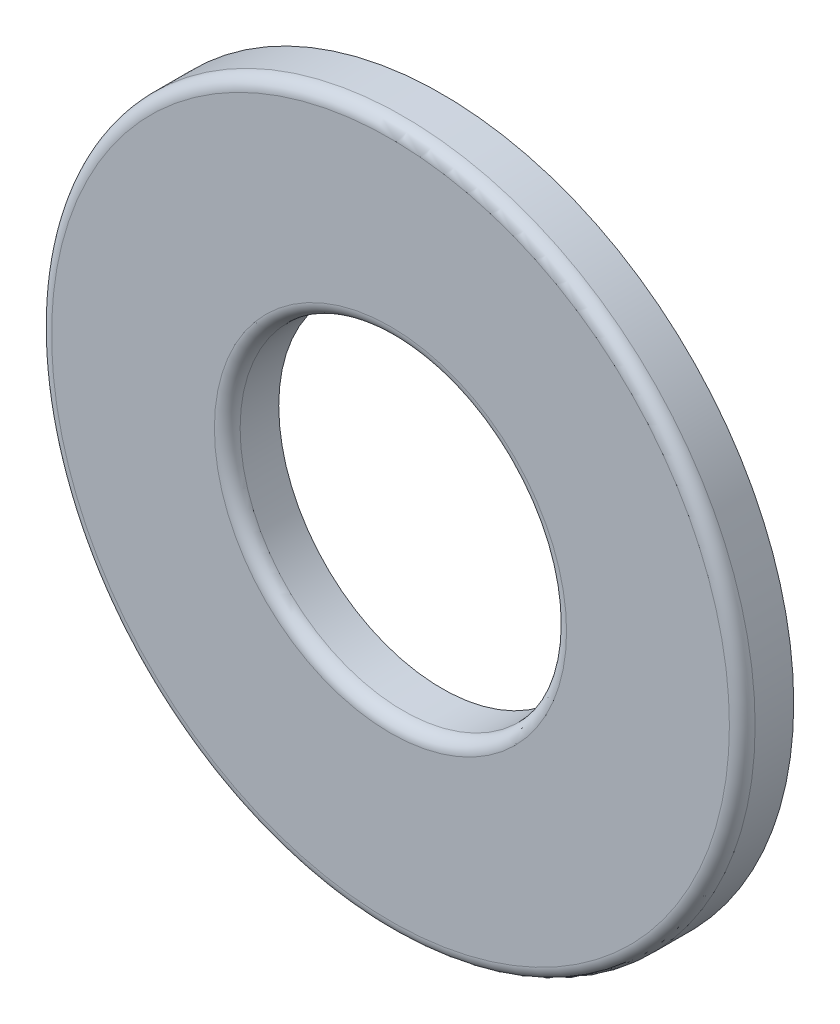
SolidWorks part; units mm, degrees
other "Imported1" parameters "D1"=0.2032, "TH"=1.0287, "Thickness"=0.8128
ref_plane "Front Plane" through (0, 0, 0) normal (0, 0, 1) x (1, 0, 0)
ref_plane "Top Plane" through (0, 0, 0) normal (0, 1, 0) x (1, 0, 0)
ref_plane "Right Plane" through (0, 0, 0) normal (1, 0, 0) x (0, 0, -1)
sketch "Sketch1" plane through (0, 0, 0) normal (0, 0, 1) x (1, 0, 0)
  line L0 (-5.5562, 0) -> (5.5562, 0) construction
  line L1 (-2.5781, 0) -> (2.5781, 0) construction
  circle A0 centre (0, 0) radius 2.5781 construction
  circle A1 centre (0, 0) radius 5.5562 construction
  point P8 (0, 0)
  point P9 (0, 5.5562)
  point P11 (2.5781, 0)
  dimension "ID" = 5.1562
  dimension "OD" = 11.1125
sketch "Sketch2" plane through (0, 0, 0) normal (1, 0, 0) x (0, 0, -1)
  line L0 (-0.4064, 5.5562) -> (0.4064, 5.5562) construction
  point P2 (0, 5.5562)
sketch "Sketch3" plane through (0, 0, 0) normal (0, 0, 1) x (1, 0, 0)
  circle A0 centre (0, 0) radius 2.5781
  circle A1 centre (0, 0) radius 5.5562
extrude "Boss-Extrude1" add sketch "Sketch3" along normal up to vertex (0.4064 mm away) and the other way up to vertex (0.4064 mm away) up to point (0, 5.5562, 0.4064) other way up to point (0, 5.5562, -0.4064)
fillet "Fillet1" radius 0.2032 2 edges at (5.5562, 0, 0.4064) (2.5781, 0, 0.4064)
equation "\"D1@Fillet1\"=\"Thickness@Sketch2\"/4"
